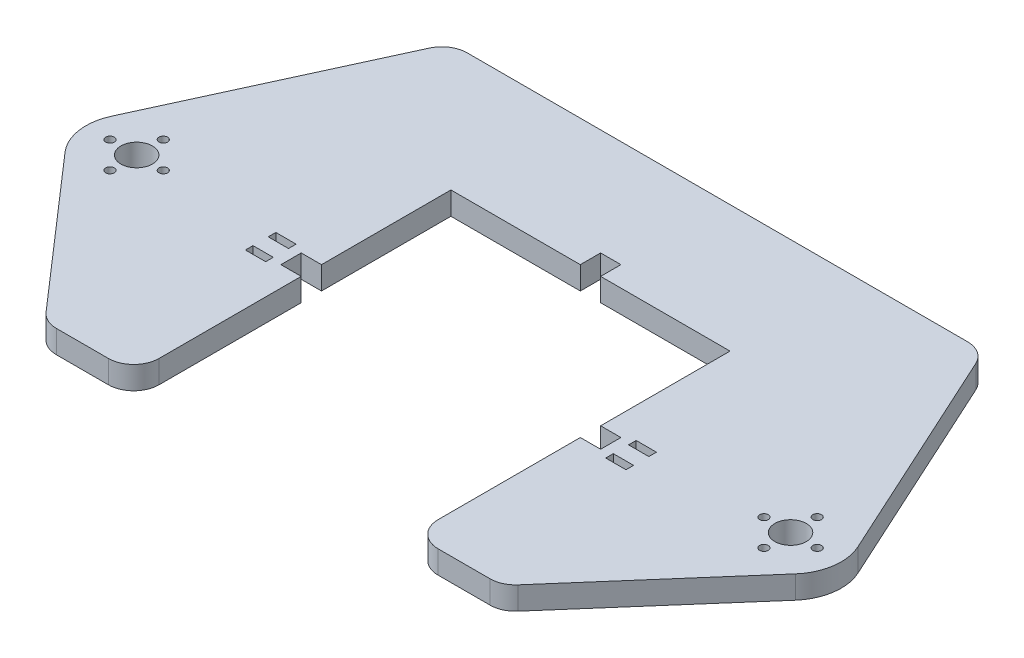
SolidWorks part; units mm, degrees
ref_plane "前视基准面" through (0, 0, 0) normal (0, 0, 1) x (1, 0, 0)
ref_plane "上视基准面" through (0, 0, 0) normal (0, 1, 0) x (1, 0, 0)
ref_plane "右视基准面" through (0, 0, 0) normal (1, 0, 0) x (0, 0, -1)
sketch "草图1" plane through (0, 0, 0) normal (0, 1, 0) x (1, 0, 0)
  line L0 (-98.5841, 105) -> (98.5841, 105)
  line L1 (-55, 55) -> (55, 55)
  line L2 (-55, 55) -> (-55, -55)
  line L4 (55, 55) -> (55, -55)
  line L5 (0, -52.5) -> (0, 55) construction
  line L6 (-55, 0) -> (55, 0) construction
  line L15 (-105, 105) -> (-105, -105) construction
  line L17 (105, 105) -> (105, -105) construction
  line L18 (-147.03, 13.3359) -> (-107.6741, 99.168)
  line L21 (147.03, 13.3359) -> (107.6741, 99.168)
  line L22 (-105, -105) -> (105, -105) construction
  line L23 (-143.9256, -8.1425) -> (-92.9891, -66.5713)
  line L24 (-85.4513, -70) -> (-55, -70)
  line L25 (143.9256, -8.1425) -> (92.9891, -66.5713)
  line L28 (50, -70) -> (85.4513, -70)
  line L29 (-55, -55) -> (55, -55) construction
  line L30 (-55, -55) -> (55, -55)
  line L31 (-55, -70) -> (50, -70)
  line L32 (-105, 105) -> (105, 105) construction
  arc A0 (-147.03, 13.3359) -> (-143.9256, -8.1425) centre (-128.85, 5) ccw
  arc A1 (147.03, 13.3359) -> (143.9256, -8.1425) centre (128.85, 5) cw
  arc A2 (-92.9891, -66.5713) -> (-85.4513, -70) centre (-85.4513, -60) ccw
  arc A3 (85.4513, -70) -> (92.9891, -66.5713) centre (85.4513, -60) ccw
  arc A4 (98.5841, 105) -> (107.6741, 99.168) centre (98.5841, 95) cw
  arc A5 (-107.6741, 99.168) -> (-98.5841, 105) centre (-98.5841, 95) cw
  point P0 (0, 0)
  point P29 (-90, -70)
  point P32 (90, -70)
  dimension "D3" = 20
  dimension "D7" = 5
  dimension "D8" = 10
  dimension "D1" = 110
  dimension "D2" = 15
  dimension "D4" = 257.7
  dimension "D5" = 50
  dimension "D6" = 180
extrude "凸台-拉伸1" add sketch "草图1" along normal blind 9
sketch "草图2" plane through (0, 9, 0) normal (0, 1, 0) x (1, 0, 0)
  circle A0 centre (-128.85, 5) radius 6.2
  circle A1 centre (128.85, 5) radius 6.2
  dimension "D1" = 12.4
  dimension "D2" = 12.4
extrude "切除-拉伸1" cut sketch "草图2" against normal blind 9
sketch "草图4" plane through (0, 0, 0) normal (0, -1, 0) x (1, 0, 0)
  line L0 (0, 61.5373) -> (0, 0) construction
  line L1 (-97, 5) -> (-87, 5)
  line L2 (-97, 5) -> (-97, -5)
  line L3 (-97, -5) -> (-87, -5)
  line L4 (-87, 5) -> (-87, -5)
  line L5 (-92, -5) -> (-92, 5) construction
  line L6 (-97, 0) -> (-87, 0) construction
  line L7 (97, 0) -> (87, 0) construction
  line L8 (92, -5) -> (92, 5) construction
  line L9 (87, 5) -> (87, -5)
  line L10 (97, -5) -> (87, -5)
  line L11 (97, 5) -> (97, -5)
  line L12 (97, 5) -> (87, 5)
  point P0 (-92, 0)
  point P17 (92, 0)
  dimension "D1" = 10
  dimension "D2" = 174
extrude "凸台-拉伸2" [suppressed] add sketch "草图4" along normal blind 30
sketch "草图5" [suppressed] plane through (87, 0, 0) normal (-1, 0, 0) x (0, 0, 1)
  circle A0 centre (0, -18.5436) radius 12.5
  dimension "D1" = 25
extrude "凸台-拉伸3" [suppressed] add sketch "草图5" against normal blind 10
mirror "镜向1" [suppressed] about plane through (0, 0, 0) normal (1, 0, 0)
sketch "草图10" plane through (0, 9, 0) normal (0, 1, 0) x (1, 0, 0)
  line L0 (-36.8172, 0) -> (44.6368, 0) construction
  line L1 (0, 48.9412) -> (0, -25.9964) construction
  line L2 (-55, 55) -> (-55, -55) construction
  line L3 (-63, 4) -> (-55, 4)
  line L4 (-63, 4) -> (-63, -4)
  line L5 (-63, -4) -> (-55, -4)
  line L6 (-55, 4) -> (-55, -4)
  line L7 (-59, -4) -> (-59, 4) construction
  line L8 (-63, 0) -> (-55, 0) construction
  line L9 (4, 63) -> (4, 55)
  line L10 (4, 63) -> (-4, 63)
  line L11 (-4, 63) -> (-4, 55)
  line L12 (4, 55) -> (-4, 55)
  line L13 (-4, 59) -> (4, 59) construction
  line L14 (0, 63) -> (0, 55) construction
  line L15 (63, -4) -> (55, -4)
  line L16 (63, -4) -> (63, 4)
  line L17 (63, 4) -> (55, 4)
  line L18 (55, -4) -> (55, 4)
  line L19 (59, 4) -> (59, -4) construction
  line L20 (63, 0) -> (55, 0) construction
  line L21 (-4, -63) -> (-4, -55)
  line L22 (-4, -63) -> (4, -63)
  line L23 (4, -63) -> (4, -55)
  line L24 (-4, -55) -> (4, -55)
  line L25 (4, -59) -> (-4, -59) construction
  line L26 (0, -63) -> (0, -55) construction
  line L27 (55, -55) -> (55, 55) construction
  point P5 (-59, 0)
  point P17 (0, 59)
  point P26 (59, 0)
  point P35 (0, -59)
  point P46 (0, 0)
  dimension "D1" = 8
  dimension "D2" = 4
extrude "切除-拉伸3" cut sketch "草图10" against normal blind 10
sketch "草图9" plane through (0, 0, 0) normal (0, -1, 0) x (1, 0, 0)
  line L0 (-55, 55) -> (-55, 70)
  line L1 (-85.4513, 70) -> (85.4513, 70) construction
  line L2 (-55, 70) -> (55, 70)
  line L3 (55, 70) -> (55, 55)
  line L4 (55, 55) -> (-55, 55)
  line L5 (-55, 55) -> (-4, 55) construction
extrude "切除-拉伸4" cut sketch "草图9" against normal blind 10
fillet "圆角1" radius 10 2 edges at (55, 4.5, 70) (-55, 4.5, 70)
sketch "草图11" plane through (0, 9, 0) normal (0, 1, 0) x (1, 0, 0)
  line L0 (67, 6) -> (75, 6)
  line L1 (67, -3) -> (75, -3)
  line L2 (67, -3) -> (67, -6)
  line L3 (67, -6) -> (75, -6)
  line L4 (75, -3) -> (75, -6)
  line L5 (71, -6) -> (71, -3) construction
  line L6 (67, -4.5) -> (75, -4.5) construction
  line L7 (67, 6) -> (67, 3)
  line L8 (67, 3) -> (75, 3)
  line L9 (75, 6) -> (75, 3)
  line L10 (71, 3) -> (71, 6) construction
  line L11 (67, 4.5) -> (75, 4.5) construction
  line L12 (63, -4) -> (63, 4) construction
  line L13 (-67, 4.5) -> (-75, 4.5) construction
  line L14 (0, 28.2191) -> (0, -31.3561) construction
  line L15 (-71, 3) -> (-71, 6) construction
  line L16 (-67, -4.5) -> (-75, -4.5) construction
  line L17 (-71, -6) -> (-71, -3) construction
  line L18 (-75, 6) -> (-75, 3)
  line L27 (-67, 3) -> (-75, 3)
  line L28 (-67, 6) -> (-67, 3)
  line L29 (55, -4) -> (63, -4) construction
  line L46 (-75, -3) -> (-75, -6)
  line L47 (-67, -6) -> (-75, -6)
  line L48 (-67, -3) -> (-67, -6)
  line L49 (-67, -3) -> (-75, -3)
  line L50 (-67, 6) -> (-75, 6)
  point P0 (71, -4.5)
  point P4 (71, 4.5)
  point P38 (-71, 4.5)
  point P39 (-71, -4.5)
  dimension "D1" = 3
  dimension "D2" = 8
  dimension "D3" = 3
  dimension "D5" = 4
  dimension "D6" = 6
  dimension "D7" = 2
extrude "切除-拉伸5" cut sketch "草图11" against normal blind 10
sketch "草图12" plane through (0, 9, 0) normal (0, 1, 0) x (1, 0, 0)
  line L0 (0, 31.0203) -> (0, 0) construction
  circle A0 centre (-128.85, 5) radius 10.5 construction
  circle A1 centre (-128.85, 15.5) radius 1.7
  circle A2 centre (-118.35, 5) radius 1.7
  circle A3 centre (-128.85, -5.5) radius 1.7
  circle A4 centre (-139.35, 5) radius 1.7
  circle A5 centre (128.85, 5) radius 10.5 construction
  circle A6 centre (139.35, 5) radius 1.7
  circle A7 centre (128.85, -5.5) radius 1.7
  circle A8 centre (118.35, 5) radius 1.7
  circle A9 centre (128.85, 15.5) radius 1.7
  point P14 (-128.85, 5)
  dimension "D1" = 21
  dimension "D2" = 3.4
  dimension "D3" = 4
extrude "切除-拉伸6" cut sketch "草图12" against normal blind 10
